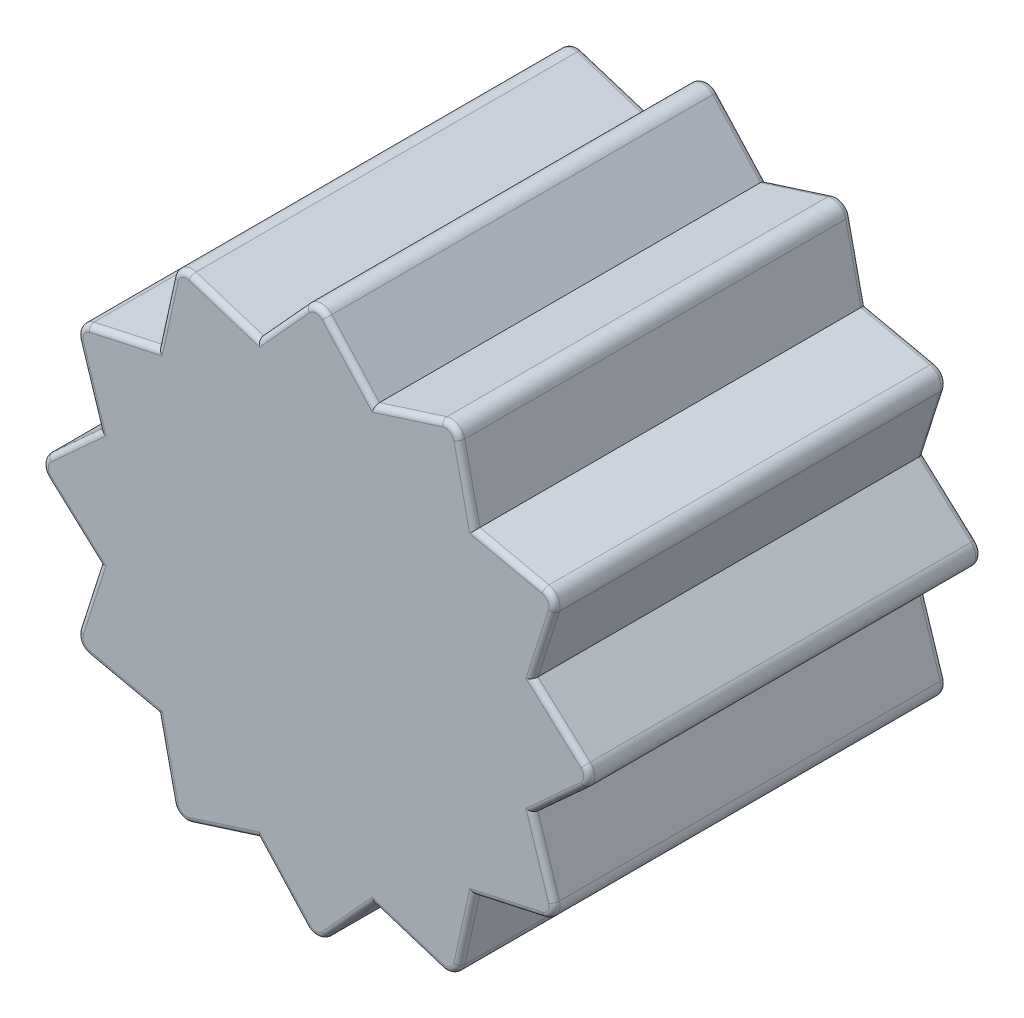
SolidWorks part; units mm, degrees
ref_plane "Front Plane" through (0, 0, 0) normal (0, 0, 1) x (1, 0, 0)
ref_plane "Top Plane" through (0, 0, 0) normal (0, 1, 0) x (1, 0, 0)
ref_plane "Right Plane" through (0, 0, 0) normal (1, 0, 0) x (0, 0, -1)
sketch "Sketch1" plane through (0, 0, 0) normal (0, 0, 1) x (1, 0, 0)
  line L0 (0, 10) -> (0, -10) construction
  line L1 (0, 0) -> (5, 8.6603) construction
  line L2 (0, 0) -> (2.0706, 7.7274) construction
  line L3 (0, 0) -> (0.6451, 7.3734) construction
  line L4 (0.3696, 9.5943) -> (2.0706, 7.7274)
  line L5 (-0.3696, 9.5943) -> (-2.0706, 7.7274)
  line L6 (0, 0) -> (-3.1598, 11.7927) construction
  line L8 (4.4771, 8.4937) -> (2.0706, 7.7274)
  line L9 (5.1173, 8.1241) -> (5.6569, 5.6569)
  line L10 (8.1241, 5.1173) -> (5.6569, 5.6569)
  line L11 (8.4937, 4.4771) -> (7.7274, 2.0706)
  line L12 (9.5943, 0.3696) -> (7.7274, 2.0706)
  line L13 (9.5943, -0.3696) -> (7.7274, -2.0706)
  line L14 (8.4937, -4.4771) -> (7.7274, -2.0706)
  line L15 (8.1241, -5.1173) -> (5.6569, -5.6569)
  line L16 (5.1173, -8.1241) -> (5.6569, -5.6569)
  line L17 (4.4771, -8.4937) -> (2.0706, -7.7274)
  line L18 (0.3696, -9.5943) -> (2.0706, -7.7274)
  line L19 (-0.3696, -9.5943) -> (-2.0706, -7.7274)
  line L20 (-4.4771, -8.4937) -> (-2.0706, -7.7274)
  line L21 (-5.1173, -8.1241) -> (-5.6569, -5.6569)
  line L22 (-8.1241, -5.1173) -> (-5.6569, -5.6569)
  line L23 (-8.4937, -4.4771) -> (-7.7274, -2.0706)
  line L24 (-9.5943, -0.3696) -> (-7.7274, -2.0706)
  line L25 (-9.5943, 0.3696) -> (-7.7274, 2.0706)
  line L26 (-8.4937, 4.4771) -> (-7.7274, 2.0706)
  line L27 (-8.1241, 5.1173) -> (-5.6569, 5.6569)
  line L28 (-5.1173, 8.1241) -> (-5.6569, 5.6569)
  line L29 (-4.4771, 8.4937) -> (-2.0706, 7.7274)
  circle A0 centre (0, 0) radius 10 construction
  arc A1 (0.3696, 9.5943) -> (-0.3696, 9.5943) centre (0, 9.2576) ccw
  arc A2 (5.1173, 8.1241) -> (4.4771, 8.4937) centre (4.6288, 8.0173) ccw
  arc A3 (8.4937, 4.4771) -> (8.1241, 5.1173) centre (8.0173, 4.6288) ccw
  arc A4 (9.5943, -0.3696) -> (9.5943, 0.3696) centre (9.2576, 0) ccw
  arc A5 (8.1241, -5.1173) -> (8.4937, -4.4771) centre (8.0173, -4.6288) ccw
  arc A6 (4.4771, -8.4937) -> (5.1173, -8.1241) centre (4.6288, -8.0173) ccw
  arc A7 (-0.3696, -9.5943) -> (0.3696, -9.5943) centre (0, -9.2576) ccw
  arc A8 (-5.1173, -8.1241) -> (-4.4771, -8.4937) centre (-4.6288, -8.0173) ccw
  arc A9 (-8.4937, -4.4771) -> (-8.1241, -5.1173) centre (-8.0173, -4.6288) ccw
  arc A10 (-9.5943, 0.3696) -> (-9.5943, -0.3696) centre (-9.2576, 0) ccw
  arc A11 (-8.1241, 5.1173) -> (-8.4937, 4.4771) centre (-8.0173, 4.6288) ccw
  arc A12 (-4.4771, 8.4937) -> (-5.1173, 8.1241) centre (-4.6288, 8.0173) ccw
  point P71 (0, 0)
  point P95 (0, 0)
  point P106 (0, 0)
  point P123 (-0.0489, -0.2306)
  dimension "D1" = 8
  dimension "D5" = 0.5
  dimension "D6" = 15
  dimension "D7" = 20
  dimension "D2" = 30
  dimension "D3" = 15
  dimension "D4" = 5
  dimension "D8" = 12
extrude "Boss-Extrude1" add sketch "Sketch1" along normal blind 14
sketch "Sketch2" plane through (0, 0, 0) normal (0, 0, -1) x (-1, 0, 0)
  line L0 (0, 0) -> (0, 6.2989) construction
  line L1 (0, 0) -> (0, 2.75) construction
  arc A1 (-1.9413, 1.9478) -> (-2.2553, 1.5736) centre (0, 0) ccw
  arc A2 (0.2351, 2.7399) -> (-0.2351, 2.7399) centre (0, 2.825) ccw
  arc A3 (1.158, 2.4943) -> (0.7162, 2.6551) centre (0.9662, 2.6546) ccw
  arc A4 (1.9413, 1.9478) -> (1.5811, 2.25) centre (1.8159, 2.1641) ccw
  arc A5 (2.4904, 1.1664) -> (2.2553, 1.5736) centre (2.4465, 1.4125) ccw
  arc A6 (2.7391, 0.2443) -> (2.6575, 0.7073) centre (2.7821, 0.4906) ccw
  arc A7 (2.6575, -0.7073) -> (2.7391, -0.2443) centre (2.7821, -0.4906) ccw
  arc A8 (2.2553, -1.5736) -> (2.4904, -1.1664) centre (2.4465, -1.4125) ccw
  arc A9 (1.5811, -2.25) -> (1.9413, -1.9478) centre (1.8159, -2.1641) ccw
  arc A10 (0.7162, -2.6551) -> (1.158, -2.4943) centre (0.9662, -2.6546) ccw
  arc A11 (-0.2351, -2.7399) -> (0.2351, -2.7399) centre (0, -2.825) ccw
  arc A12 (-1.158, -2.4943) -> (-0.7162, -2.6551) centre (-0.9662, -2.6546) ccw
  arc A13 (-1.9413, -1.9478) -> (-1.5811, -2.25) centre (-1.8159, -2.1641) ccw
  arc A14 (-2.4904, -1.1664) -> (-2.2553, -1.5736) centre (-2.4465, -1.4125) ccw
  arc A15 (-2.7391, -0.2443) -> (-2.6575, -0.7073) centre (-2.7821, -0.4906) ccw
  arc A16 (-2.6575, 0.7073) -> (-2.7391, 0.2443) centre (-2.7821, 0.4906) ccw
  arc A17 (-2.2553, 1.5736) -> (-2.4904, 1.1664) centre (-2.4465, 1.4125) ccw
  arc A18 (-1.5811, 2.25) -> (-1.9413, 1.9478) centre (-1.8159, 2.1641) ccw
  arc A19 (-0.7162, 2.6551) -> (-1.158, 2.4943) centre (-0.9662, 2.6546) ccw
  arc A20 (-1.158, 2.4943) -> (-1.5811, 2.25) centre (0, 0) ccw
  arc A21 (-0.2351, 2.7399) -> (-0.7162, 2.6551) centre (0, 0) ccw
  arc A22 (0.7162, 2.6551) -> (0.2351, 2.7399) centre (0, 0) ccw
  arc A23 (1.5811, 2.25) -> (1.158, 2.4943) centre (0, 0) ccw
  arc A24 (2.2553, 1.5736) -> (1.9413, 1.9478) centre (0, 0) ccw
  arc A25 (2.6575, 0.7073) -> (2.4904, 1.1664) centre (0, 0) ccw
  arc A26 (2.7391, -0.2443) -> (2.7391, 0.2443) centre (0, 0) ccw
  arc A27 (2.4904, -1.1664) -> (2.6575, -0.7073) centre (0, 0) ccw
  arc A28 (1.9413, -1.9478) -> (2.2553, -1.5736) centre (0, 0) ccw
  arc A29 (1.158, -2.4943) -> (1.5811, -2.25) centre (0, 0) ccw
  arc A30 (0.2351, -2.7399) -> (0.7162, -2.6551) centre (0, 0) ccw
  arc A31 (-0.7162, -2.6551) -> (-0.2351, -2.7399) centre (0, 0) ccw
  arc A32 (-1.5811, -2.25) -> (-1.158, -2.4943) centre (0, 0) ccw
  arc A33 (-2.2553, -1.5736) -> (-1.9413, -1.9478) centre (0, 0) ccw
  arc A34 (-2.6575, -0.7073) -> (-2.4904, -1.1664) centre (0, 0) ccw
  arc A35 (-2.7391, 0.2443) -> (-2.7391, -0.2443) centre (0, 0) ccw
  arc A36 (-2.4904, 1.1664) -> (-2.6575, 0.7073) centre (0, 0) ccw
  point P43 (0, 3.075)
  point P60 (0, -3.075)
  dimension "D1" = 5.5
  dimension "D3" = 0.5
  dimension "D2" = 2.825
  dimension "D4" = 3.075
  dimension "D5" = 6.15
extrude "Cut-Extrude1" cut sketch "Sketch2" against normal blind 11
fillet "Fillet1" radius 0.2 91 edges at (-6.8905, 5.3871, 0) (-5.3871, -6.8905, 0) (1.2201, 8.6609, 0) (1.2201, 8.6609, 14) (-5.3871, -6.8905, 14) (0.4775, 2.7082, 0) (3.0283, -0.534, 0) (2.663, -1.5375, 0) (1.9766, -2.3556, 0) (1.0517, -2.8896, 0) (-1.0517, -2.8896, 0) (-1.9766, -2.3556, 0) (-3.0283, -0.534, 0) (-3.0283, 0.534, 0) (-2.663, 1.5375, 0) (-1.9766, 2.3556, 0) (-1.0517, 2.8896, 0) (0, 3.075, 0) (1.0517, 2.8896, 0) (1.9766, 2.3556, 0) (2.663, 1.5375, 0) (3.0283, 0.534, 0) (2.5842, 0.9406, 0) (2.75, 0, 0) (2.5842, -0.9406, 0) (2.1066, -1.7677, 0) (1.375, -2.3816, 0) (0.4775, -2.7082, 0) (-0.4775, -2.7082, 0) (-1.375, -2.3816, 0) (-2.5842, -0.9406, 0) (-2.75, 0, 0) (-2.5842, 0.9406, 0) (-2.1066, 1.7677, 0) (-1.375, 2.3816, 0) (1.375, 2.3816, 0) (2.1066, 1.7677, 0) (-4.8788, 8.4503, 0) (-5.3871, 6.8905, 0) (-8.1106, 3.2738, 0) (-8.6609, 1.2201, 0) (-9.7576, 0, 0) (-8.6609, -1.2201, 0) (-6.8905, -5.3871, 0) (-1.2201, -8.6609, 0) (0, -9.7576, 0) (1.2201, -8.6609, 0) (3.2738, -8.1106, 0) (4.8788, -8.4503, 0) (5.3871, -6.8905, 0) (6.8905, -5.3871, 0) (8.4503, -4.8788, 0) (8.1106, -3.2738, 0) (8.6609, -1.2201, 0) (9.7576, 0, 0) (8.6609, 1.2201, 0) (8.1106, 3.2738, 0) (6.8905, 5.3871, 0) (5.3871, 6.8905, 0) (4.8788, 8.4503, 0) (3.2738, 8.1106, 0) (0, 9.7576, 0) (-1.2201, 8.6609, 0) (-3.2738, 8.1106, 0) (-1.2201, 8.6609, 14) (0, 9.7576, 14) (3.2738, 8.1106, 14) (4.8788, 8.4503, 14) (5.3871, 6.8905, 14) (6.8905, 5.3871, 14) (8.4503, 4.8788, 14) (8.1106, 3.2738, 14) (9.7576, 0, 14) (8.6609, -1.2201, 14) (8.1106, -3.2738, 14) (8.4503, -4.8788, 14) (5.3871, -6.8905, 14) (4.8788, -8.4503, 14) (3.2738, -8.1106, 14) (1.2201, -8.6609, 14) (0, -9.7576, 14) (-1.2201, -8.6609, 14) (-4.8788, -8.4503, 14) (-6.8905, -5.3871, 14) (-8.4503, -4.8788, 14) (-8.1106, -3.2738, 14) (-8.6609, -1.2201, 14) (-9.7576, 0, 14) (-8.1106, 3.2738, 14) (-8.4503, 4.8788, 14) (-3.2738, 8.1106, 14)
sketch "Sketch4" plane through (0, 0, 0) normal (0, 0, -1) x (-1, 0, 0)
  circle A0 centre (0, 0) radius 3.5
  dimension "D1" = 7
extrude "Cut-Extrude2" cut sketch "Sketch4" against normal blind 0.6
fillet "Fillet42" radius 0.1 109 edges at (2.1066, 1.7677, 0.6) (2.663, 1.5375, 0.6) (2.5842, 0.9406, 0.6) (3.0283, 0.534, 0.6) (2.75, 0, 0.6) (3.0283, -0.534, 0.6) (2.5842, -0.9406, 0.6) (2.663, -1.5375, 0.6) (2.1066, -1.7677, 0.6) (1.9766, -2.3556, 0.6) (1.375, -2.3816, 0.6) (1.0517, -2.8896, 0.6) (0.4775, -2.7082, 0.6) (0, -3.075, 0.6) (-0.4775, -2.7082, 0.6) (-1.0517, -2.8896, 0.6) (-1.375, -2.3816, 0.6) (-1.9766, -2.3556, 0.6) (-2.1066, -1.7677, 0.6) (-2.663, -1.5375, 0.6) (-2.5842, -0.9406, 0.6) (-3.0283, -0.534, 0.6) (-2.75, 0, 0.6) (-3.0283, 0.534, 0.6) (-2.5842, 0.9406, 0.6) (-2.663, 1.5375, 0.6) (-2.1066, 1.7677, 0.6) (-1.9766, 2.3556, 0.6) (-1.375, 2.3816, 0.6) (-1.0517, 2.8896, 0.6) (-0.4775, 2.7082, 0.6) (0, 3.075, 0.6) (0.4775, 2.7082, 0.6) (1.0517, 2.8896, 0.6) (1.375, 2.3816, 0.6) (1.9766, 2.3556, 0.6) (-3.5, 0, 0.6) (-2.1066, -1.7677, 11) (-2.5842, -0.9406, 11) (-2.75, 0, 11) (-2.5842, 0.9406, 11) (-2.1066, 1.7677, 11) (-1.375, 2.3816, 11) (-0.4775, 2.7082, 11) (0.4775, 2.7082, 11) (1.375, 2.3816, 11) (2.1066, 1.7677, 11) (2.5842, 0.9406, 11) (2.75, 0, 11) (2.5842, -0.9406, 11) (2.1066, -1.7677, 11) (1.375, -2.3816, 11) (0.4775, -2.7082, 11) (-0.4775, -2.7082, 11) (-1.375, -2.3816, 11) (-1.5811, -2.25, 5.8) (-1.9766, -2.3556, 11) (-1.9413, -1.9478, 5.8) (-2.2553, -1.5736, 5.8) (-2.663, -1.5375, 11) (-2.4904, -1.1664, 5.8) (-2.6575, -0.7073, 5.8) (-3.0283, -0.534, 11) (-2.7391, -0.2443, 5.8) (-2.7391, 0.2443, 5.8) (-3.0283, 0.534, 11) (-2.6575, 0.7073, 5.8) (-2.4904, 1.1664, 5.8) (-2.663, 1.5375, 11) (-2.2553, 1.5736, 5.8) (-1.9413, 1.9478, 5.8) (-1.9766, 2.3556, 11) (-1.5811, 2.25, 5.8) (-1.158, 2.4943, 5.8) (-1.0517, 2.8896, 11) (-0.7162, 2.6551, 5.8) (-0.2351, 2.7399, 5.8) (0, 3.075, 11) (0.2351, 2.7399, 5.8) (0.7162, 2.6551, 5.8) (1.0517, 2.8896, 11) (1.158, 2.4943, 5.8) (1.5811, 2.25, 5.8) (1.9766, 2.3556, 11) (1.9413, 1.9478, 5.8) (2.2553, 1.5736, 5.8) (2.663, 1.5375, 11) (2.4904, 1.1664, 5.8) (2.6575, 0.7073, 5.8) (3.0283, 0.534, 11) (2.7391, 0.2443, 5.8) (2.7391, -0.2443, 5.8) (3.0283, -0.534, 11) (2.6575, -0.7073, 5.8) (2.4904, -1.1664, 5.8) (2.663, -1.5375, 11) (2.2553, -1.5736, 5.8) (1.9413, -1.9478, 5.8) (1.9766, -2.3556, 11) (1.5811, -2.25, 5.8) (1.158, -2.4943, 5.8) (1.0517, -2.8896, 11) (0.7162, -2.6551, 5.8) (0.2351, -2.7399, 5.8) (0, -3.075, 11) (-0.2351, -2.7399, 5.8) (-0.7162, -2.6551, 5.8) (-1.0517, -2.8896, 11) (-1.158, -2.4943, 5.8)
